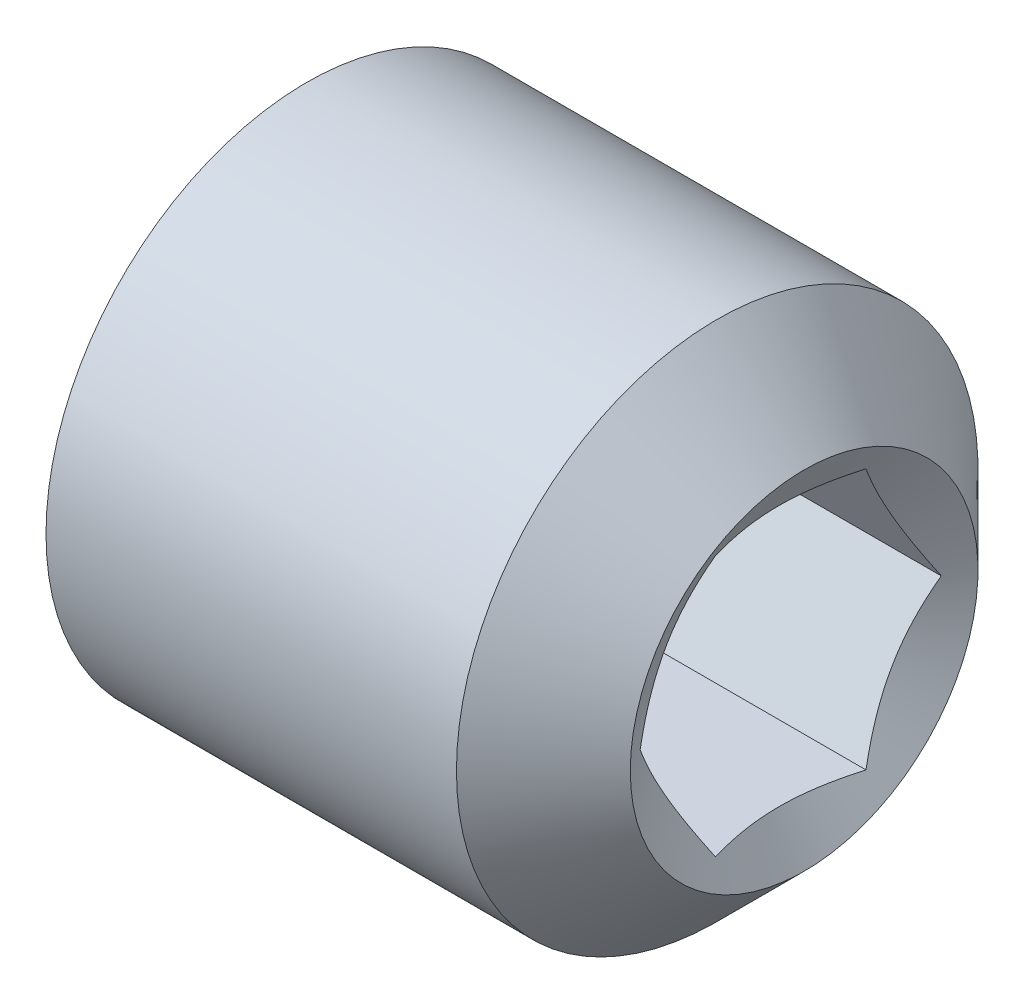
SolidWorks part; units mm, degrees
revolve "BaseBody" add sketch "BodySke" angle 360 about L5
sketch "BodySke" plane through (0, 0, 0) normal (0, 0, 1) x (1, 0, 0)
  line L0 (0, 0) -> (0, 5.036)
  line L1 (0, 5.036) -> (0.5566, 6)
  line L2 (0.5566, 6) -> (10, 6)
  line L3 (10, 6) -> (12, 4)
  line L4 (9.6906, 0) -> (0, 0)
  line L5 (-12.7, 0) -> (88.9, 0) construction
  line L6 (9.6906, 0) -> (12, 4)
  line L7 (12, 4) -> (12, 13.525) construction
  line L8 (0, -5.036) -> (0.5566, -6) construction
  line L9 (9.6906, 0) -> (12, -4) construction
  line L10 (10, -6) -> (12, -4) construction
  line L11 (0.875, 15.875) -> (0.875, -3.175) construction
  dimension "Diameter" = 12
  dimension "Drive_ch_ang" = 60
  dimension "Minor_dia" = 10.072
  dimension "Cup_ang" = 120
  dimension "Cup_dia" = 8
  dimension "Length" = 12
  dimension "Cup_nose_ang" = 45
  dimension "Advance" = 1.75
cosmetic thread "ThreadCosmetic" [suppressed] parameters "Thread_minor"=10.072
cosmetic thread "Représentation de filetage1" parameters "D2"=10.072
ref_plane "Plane1" through (0, 0, 0) normal (0, 0, 1) x (1, 0, 0)
ref_plane "Plane2" through (0, 0, 0) normal (0, 1, 0) x (1, 0, 0)
ref_plane "Plane3" through (0, 0, 0) normal (1, 0, 0) x (0, 0, -1)
sketch "Sketch2" plane through (0, 0, 0) normal (-1, 0, 0) x (0, 0, 1)
  line L0 (1.7321, 3) -> (-1.7321, 3)
  line L1 (-1.7321, 3) -> (-3.4641, 0)
  line L2 (1.7321, 3) -> (3.4641, 0)
  line L3 (1.7321, -3) -> (3.4641, 0)
  line L4 (1.7321, -3) -> (-1.7321, -3)
  line L5 (-1.7321, -3) -> (-3.4641, 0)
  dimension "Hex_size" = 6
  dimension "D2" = 3
  dimension "D3" = 3
extrude "Hex" cut sketch "Sketch2" against normal through all
sketch "ThdSchSke" plane through (0, 0, 0) normal (0, 0, 1) x (1, 0, 0)
  line L0 (0.5566, -5.036) -> (-0.1184, -6)
  line L1 (0.5566, -5.036) -> (1.2316, -6)
  line L2 (1.2316, -6) -> (1.2316, -7.5)
  line L3 (-3.175, 0) -> (5.1513, 0) construction
  line L4 (0.5566, 6) -> (0.5566, -6) construction
  line L5 (1.2316, -7.5) -> (-0.1184, -7.5)
  line L6 (-0.1184, -7.5) -> (-0.1184, -6)
  dimension "Thread_minor" = 10.072
  dimension "Diameter" = 12
revolve "ThreadSchematic" [suppressed] cut sketch "ThdSchSke" angle 360 about L3
pattern_linear "ThdSchPat" [suppressed]
equation "\"D2@Sketch2\" = \"Hex_size@Sketch2\" / 2"
equation "\"D3@Sketch2\" = \"Hex_size@Sketch2\" / 2"
equation "\"Thread_minor@ThreadCosmetic\" = \"Minor_dia@BodySke\""
equation "\"Thread_minor@ThdSchSke\" = \"Thread_minor@ThreadCosmetic\""
equation "\"Diameter@ThdSchSke\" = \"Diameter@BodySke\""
equation "\"Overcut@ThdSchSke\" = \"Diameter@BodySke\" * 1.25"
equation "\"Num_threads@ThdSchPat\" = int( (\"Length@BodySke\" - ( ( ( \"Diameter@BodySke\" - \"Minor_dia@BodySke\" ) * 0.5 ) / tan( \"Drive_ch_ang@BodySke\" * 0.017453292 ) ) - ( ( ( \"Diameter@BodySke\" - \"Cup_dia@BodySke\" ) * 0.5 ) * tan( \"Cup_nose_ang@BodySke\" * 0.017453292 ) ) ) / \"Advance@BodySke\" + 0.999 )  + 1"
equation "\"Advance@ThdSchPat\" = (\"Length@BodySke\" - ( ( ( \"Diameter@BodySke\" - \"Minor_dia@BodySke\" ) * 0.5 ) / tan( \"Drive_ch_ang@BodySke\" * 0.017453292 ) ) - ( ( ( \"Diameter@BodySke\" - \"Cup_dia@BodySke\" ) * 0.5 ) * tan( \"Cup_nose_ang@BodySke\" * 0.017453292 ) ) ) /  (\"Num_threads@ThdSchPat\" - 1) 'relax it"
equation "' \"Num_threads@ThdSchPat\" = \"Num_threads@ThdSchPat\" - sgn( \"Num_threads@ThdSchPat\" - 1) '---chamfered tips only---"
